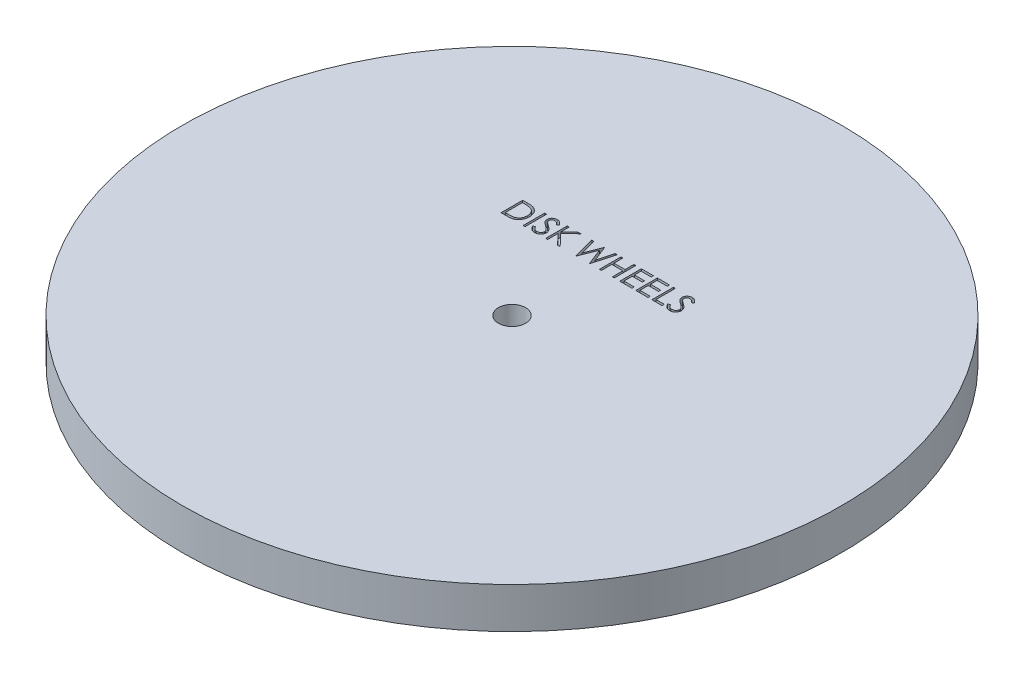
SolidWorks part; units mm, degrees
ref_plane "Front Plane" through (0, 0, 0) normal (0, 0, 1) x (1, 0, 0)
ref_plane "Top Plane" through (0, 0, 0) normal (0, 1, 0) x (1, 0, 0)
ref_plane "Right Plane" through (0, 0, 0) normal (1, 0, 0) x (0, 0, -1)
sketch "Sketch1" plane through (0, 0, 0) normal (0, 1, 0) x (1, 0, 0)
  circle A0 centre (0, 0) radius 48.5
  dimension "D1" = 97
extrude "Boss-Extrude1" add sketch "Sketch1" along normal blind 6
sketch "Sketch2" plane through (0, 6, 0) normal (0, 1, 0) x (1, 0, 0)
  text T0 "DISK WHEELS "
extrude "Cut-Extrude1" cut sketch "Sketch2" against normal blind 1
sketch "Sketch3" plane through (0, 6, 0) normal (0, 1, 0) x (1, 0, 0)
  circle A0 centre (0, 0) radius 2
  dimension "D1" = 4
extrude "Cut-Extrude2" cut sketch "Sketch3" against normal blind 10
